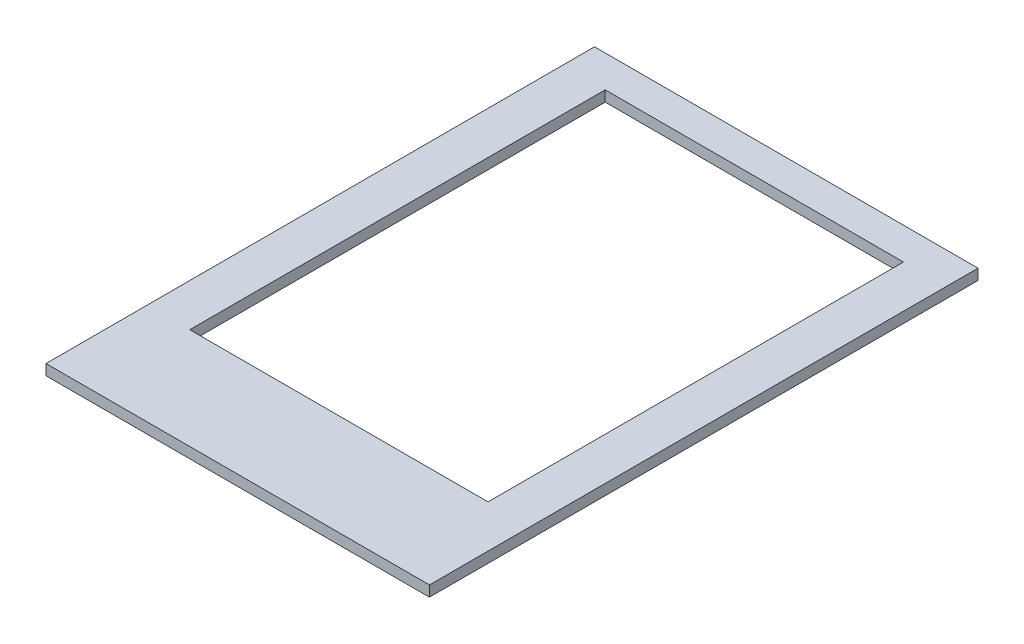
SolidWorks part; units mm, degrees
ref_plane "Front Plane" through (0, 0, 0) normal (0, 0, 1) x (1, 0, 0)
ref_plane "Top Plane" through (0, 0, 0) normal (0, 1, 0) x (1, 0, 0)
ref_plane "Right Plane" through (0, 0, 0) normal (1, 0, 0) x (0, 0, -1)
sketch "Sketch1" plane through (0, 0, 0) normal (0, 1, 0) x (1, 0, 0)
  line L1 (0, 0) -> (457.2, 0)
  line L2 (0, 0) -> (0, 654.05)
  line L3 (0, 654.05) -> (457.2, 654.05)
  line L4 (457.2, 0) -> (457.2, 654.05)
  line L5 (50.8, 615.95) -> (406.4, 615.95)
  line L6 (50.8, 615.95) -> (50.8, 120.65)
  line L7 (50.8, 120.65) -> (406.4, 120.65)
  line L8 (406.4, 615.95) -> (406.4, 120.65)
  dimension "D1" = 654.05
  dimension "D2" = 457.2
  dimension "D3" = 38.1
  dimension "D4" = 495.3
  dimension "D5" = 355.6
  dimension "D6" = 50.8
extrude "Boss-Extrude1" add sketch "Sketch1" along normal blind 12.7
equation "\"D6@Sketch1\"=(\"D2@Sketch1\"-\"D5@Sketch1\")/2"
